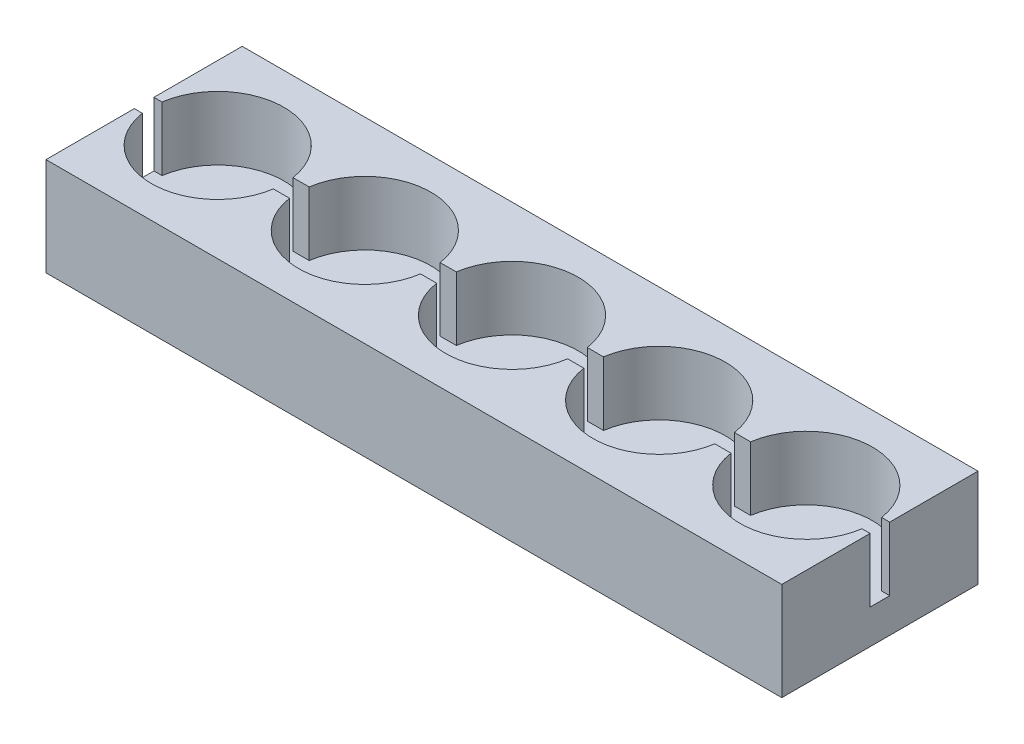
SolidWorks part; units mm, degrees
ref_plane "Front Plane" through (0, 0, 0) normal (0, 0, 1) x (1, 0, 0)
ref_plane "Top Plane" through (0, 0, 0) normal (0, 1, 0) x (1, 0, 0)
ref_plane "Right Plane" through (0, 0, 0) normal (1, 0, 0) x (0, 0, -1)
sketch "Sketch2" plane through (0, 0, 0) normal (0, 1, 0) x (1, 0, 0)
  line L1 (-75, 20) -> (75, 20)
  line L2 (-75, 20) -> (-75, -20)
  line L3 (-75, -20) -> (75, -20)
  line L4 (75, 20) -> (75, -20)
  line L5 (-75, 20) -> (75, -20) construction
  line L6 (-75, -20) -> (75, 20) construction
  point P0 (0, 0)
  dimension "D1" = 150
  dimension "D2" = 40
extrude "Boss-Extrude1" add sketch "Sketch2" along normal blind 20
sketch "Sketch3" plane through (0, 20, 0) normal (0, 1, 0) x (1, 0, 0)
  line L0 (-75, 20) -> (-75, -20) construction
  line L1 (75, 20) -> (-75, 20) construction
  circle A0 centre (-60, 0) radius 13.5
  dimension "D3" = 27
  dimension "D1" = 15
  dimension "D2" = 20
extrude "Cut-Extrude1" cut sketch "Sketch3" against normal blind 13
pattern_linear "LPattern1" count 5 spacing 30 along (1, 0, 0) of "Cut-Extrude1"
hole_wizard "CBORE for M4 Hex Socket Head Cap Screw1" positions "Sketch6" profile "Sketch5" counterbore size "M4" standard "DIN" end condition through all
sketch "Sketch6" plane through (0, 7, 0) normal (0, 1, 0) x (-1, 0, 0)
  circle A0 centre (60, 0) radius 13.5 construction
  point P0 (60, 0)
  dimension "D2" = 0
  dimension "D1" = 0
sketch "Sketch5" plane through (-60, 7, 0) normal (1, 0, 0) x (0, 0, 1)
  line L0 (0, 0) -> (0, 7)
  line L1 (0, 7) -> (2.25, 7)
  line L3 (2.25, 7) -> (2.25, 4.4)
  line L4 (2.25, 4.4) -> (4, 4.4)
  line L5 (4, 4.4) -> (4, 0)
  line L7 (4, 0) -> (0, 0)
  line L11 (0, -6.35) -> (0, 107.95) construction
  dimension "Thru Hole Dia." = 4.5
  dimension "Thru Hole Depth" = 7
  dimension "C'Bore Dia." = 8
  dimension "C'Bore Depth" = 4.4
pattern_linear "LPattern2" count 2 spacing 120 along (1, 0, 0) of "CBORE for M4 Hex Socket Head Cap Screw1"
sketch "Sketch7" plane through (0, 20, 0) normal (0, 1, 0) x (1, 0, 0)
  line L1 (-90.5645, -2) -> (90.5645, -2)
  line L2 (-90.5645, -2) -> (-90.5645, 2)
  line L3 (-90.5645, 2) -> (90.5645, 2)
  line L4 (90.5645, -2) -> (90.5645, 2)
  line L5 (-90.5645, -2) -> (90.5645, 2) construction
  line L6 (-90.5645, 2) -> (90.5645, -2) construction
  point P0 (0, 0)
  dimension "D1" = 4
extrude "Cut-Extrude3" cut sketch "Sketch7" against normal blind 13
